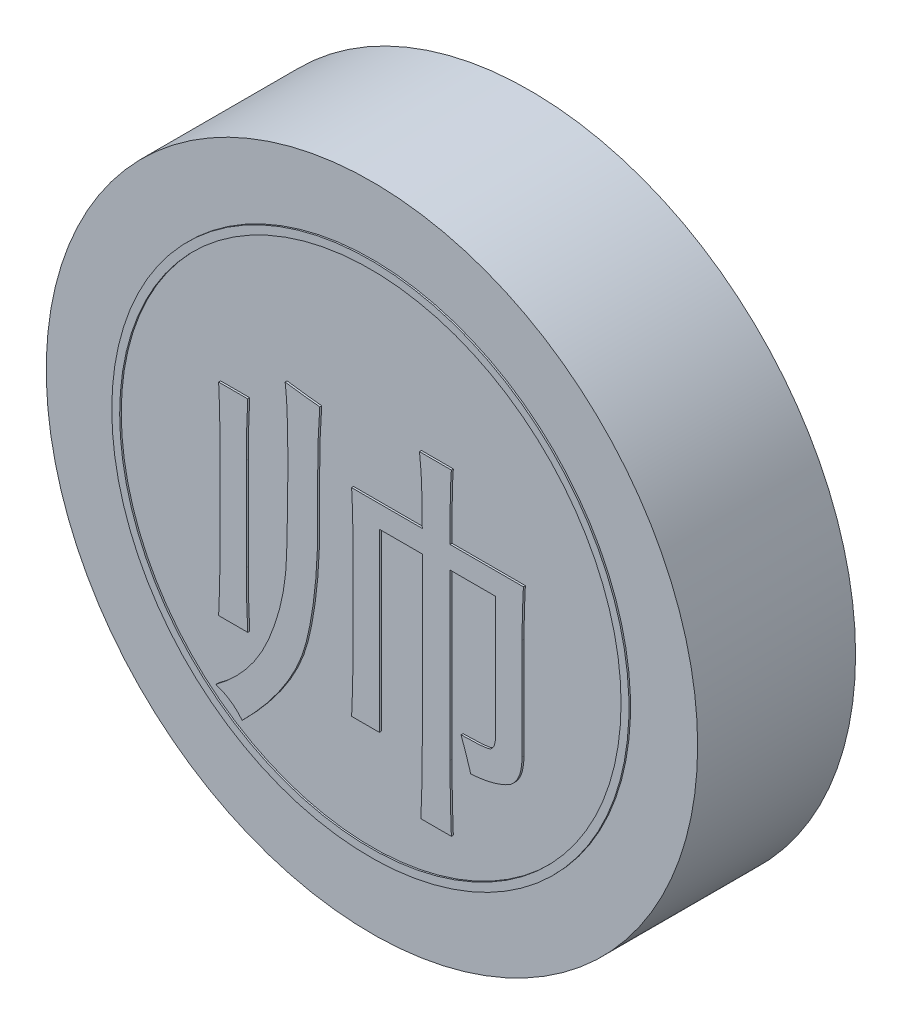
SolidWorks part; units mm, degrees
ref_plane "前视基准面" through (0, 0, 0) normal (0, 0, 1) x (1, 0, 0)
ref_plane "上视基准面" through (0, 0, 0) normal (0, 1, 0) x (1, 0, 0)
ref_plane "右视基准面" through (0, 0, 0) normal (1, 0, 0) x (0, 0, -1)
other "Configuration Table"
sketch "草图1" plane through (0, 0, 0) normal (0, 0, 1) x (1, 0, 0)
  circle A0 centre (0, 0) radius 16.5
  dimension "D1" = 33
extrude "Diameter33_Height8" add sketch "草图1" against normal blind 8
sketch "草图2" plane through (0, 0, 0) normal (0, 0, 1) x (1, 0, 0)
  text T0 "帅" font "SimHei" height 12
extrude "Character_帅" add sketch "草图2" along normal blind 0.1
sketch "草图3" plane through (0, 0, 0) normal (0, 0, 1) x (1, 0, 0)
  circle A0 centre (0, 0) radius 13.1
  circle A1 centre (0, 0) radius 12.7
extrude "Ink_ring" add sketch "草图3" along normal blind 0.08
